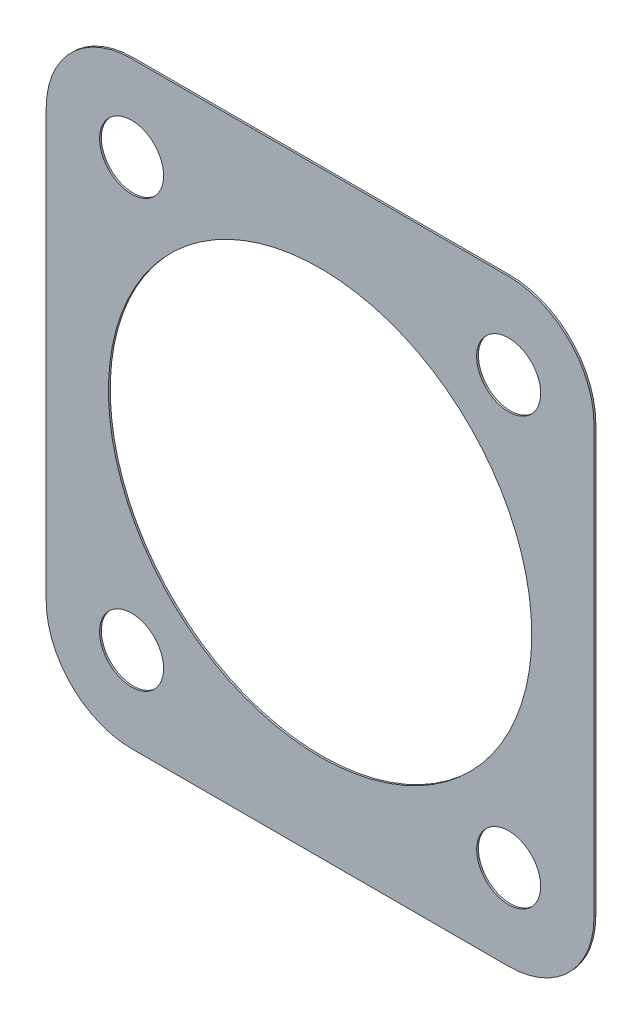
SolidWorks part; units mm, degrees
material "TESNIT BA-GL"
ref_plane "Front Plane" through (0, 0, 0) normal (0, 0, 1) x (1, 0, 0)
ref_plane "Top Plane" through (0, 0, 0) normal (0, 1, 0) x (1, 0, 0)
ref_plane "Right Plane" through (0, 0, 0) normal (1, 0, 0) x (0, 0, -1)
sketch "Sketch1" plane through (0, 0, 0) normal (0, 0, 1) x (1, 0, 0)
  line L0 (0, 0) -> (86.4235, 0) construction
  line L1 (-53, 84) -> (53, 84)
  line L2 (-77, 60) -> (-77, -60)
  line L3 (-53, -84) -> (53, -84)
  line L4 (77, 60) -> (77, -60)
  line L5 (0, 0) -> (0, 45.8327) construction
  arc A0 (77, -60) -> (53, -84) centre (53, -60) cw
  arc A1 (-53, -84) -> (-77, -60) centre (-53, -60) cw
  arc A2 (-77, 60) -> (-53, 84) centre (-53, 60) cw
  arc A3 (53, 84) -> (77, 60) centre (53, 60) cw
  circle A4 centre (53, 60) radius 9
  circle A5 centre (-53, 60) radius 9
  circle A6 centre (53, -60) radius 9
  circle A7 centre (-53, -60) radius 9
  circle A8 centre (0, 0) radius 59.5
  dimension "D1" = 24
  dimension "D2" = 120
  dimension "D3" = 106
  dimension "D4" = 18
  dimension "D5" = 119
extrude "Boss-Extrude1" add sketch "Sketch1" along normal blind 0.5
